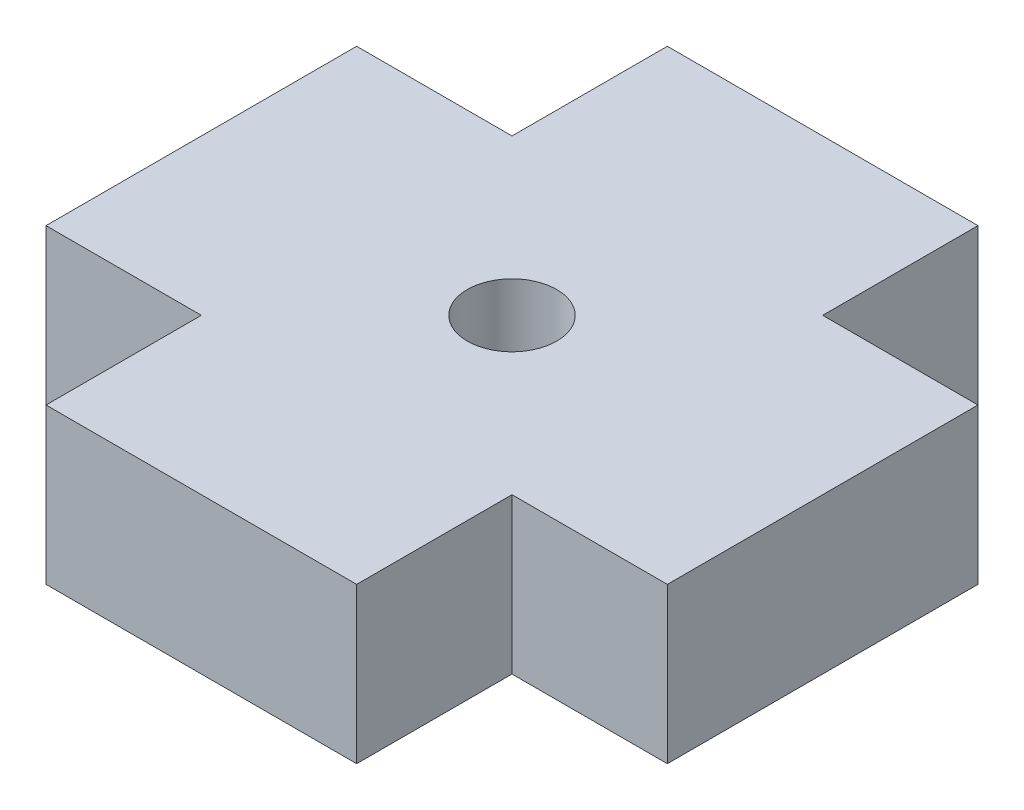
SolidWorks part; units mm, degrees
ref_plane "Front Plane" through (0, 0, 0) normal (0, 0, 1) x (1, 0, 0)
ref_plane "Top Plane" through (0, 0, 0) normal (0, 1, 0) x (1, 0, 0)
ref_plane "Right Plane" through (0, 0, 0) normal (1, 0, 0) x (0, 0, -1)
sketch "Sketch1" plane through (0, 0, 0) normal (0, 1, 0) x (1, 0, 0)
  line L0 (0, 0) -> (12.7, -25.4) construction
  line L1 (0, 0) -> (12.7, 0)
  line L2 (0, 0) -> (0, -25.4)
  line L3 (0, -25.4) -> (12.7, -25.4)
  line L4 (12.7, 0) -> (12.7, -25.4)
  line L5 (0, -12.7) -> (12.7, -12.7) construction
  line L6 (0, -12.7) -> (-6.35, -12.7) construction
  line L7 (12.7, -19.05) -> (19.05, -19.05)
  line L8 (12.7, -19.05) -> (12.7, -6.35)
  line L9 (12.7, -6.35) -> (19.05, -6.35)
  line L10 (19.05, -19.05) -> (19.05, -6.35)
  line L11 (0, -6.35) -> (-6.35, -6.35)
  line L12 (0, -6.35) -> (0, -19.05)
  line L13 (0, -19.05) -> (-6.35, -19.05)
  line L14 (-6.35, -6.35) -> (-6.35, -19.05)
  line L15 (12.7, -12.7) -> (19.05, -12.7) construction
  circle A0 centre (6.35, -12.7) radius 1.8288
  dimension "D3" = 3.6576
  dimension "D1" = 25.4
  dimension "D2" = 12.7
  dimension "D4" = 6.35
  dimension "D5" = 12.7
extrude "Boss-Extrude1" add sketch "Sketch1" along normal blind 6.35 contours L4 L1 L2 L3 A0 | L7 L10 L9 L4 | L11 L14 L13 L2
